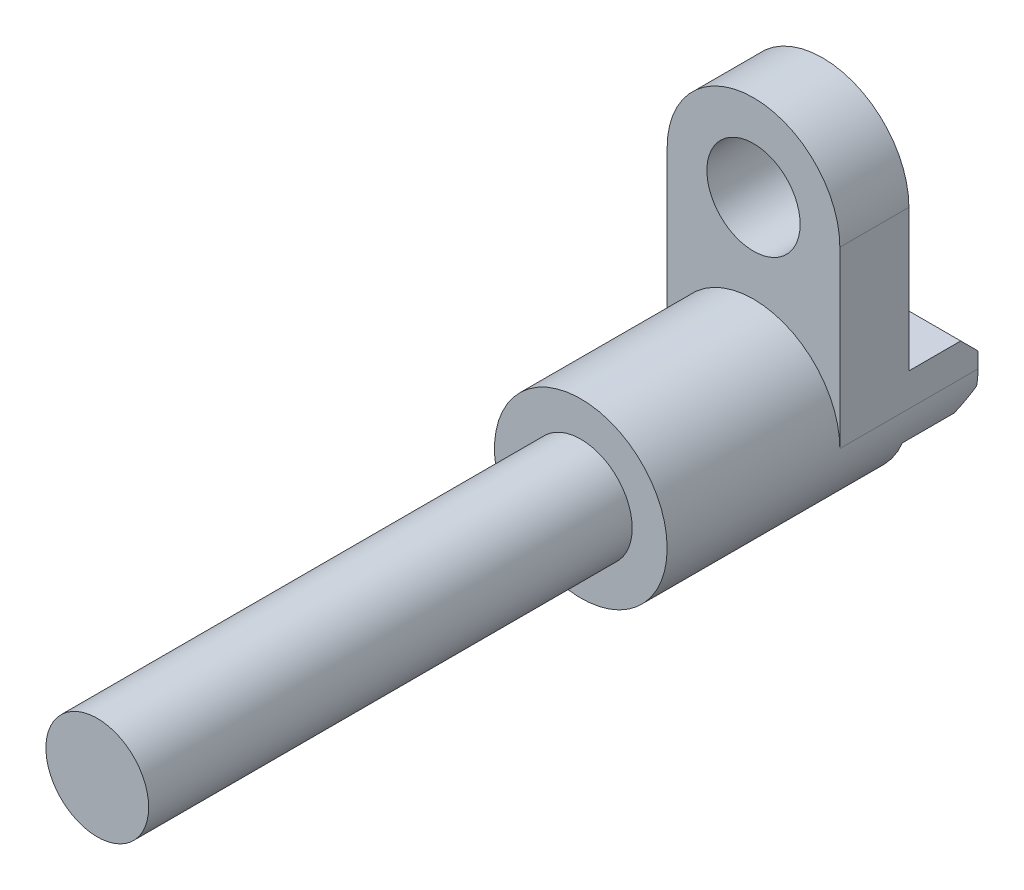
SolidWorks part; units mm, degrees
ref_plane "Front Plane" through (0, 0, 0) normal (0, 0, 1) x (1, 0, 0)
ref_plane "Top Plane" through (0, 0, 0) normal (0, 1, 0) x (1, 0, 0)
ref_plane "Right Plane" through (0, 0, 0) normal (1, 0, 0) x (0, 0, -1)
sketch "Sketch1" plane through (0, 0, 0) normal (0, 0, 1) x (1, 0, 0)
  line L0 (0, 8.6622) -> (0, -3.4189) construction
  line L1 (-7.9189, 0) -> (8.3514, 0) construction
  line L2 (-4.0536, 5.05) -> (5.1077, 5.05) construction
  line L4 (-2.5, 5.05) -> (-2.5, 0)
  line L6 (2.5, 5.05) -> (2.5, 0)
  circle A0 centre (0, 5.05) radius 1.35
  arc A1 (2.5, 5.05) -> (-2.5, 5.05) centre (0, 5.05) ccw
  arc A2 (-2.5, 0) -> (2.5, 0) centre (0, 0) ccw
  dimension "D6" = 2.7
  dimension "D1" = 2.5
  dimension "D2" = 5.05
extrude "Boss-Extrude1" add sketch "Sketch1" along normal blind 2
sketch "Sketch2" plane through (0, 0, 2) normal (0, 0, 1) x (1, 0, 0)
  line L0 (0, 8.1991) -> (0, -3.0689) construction
  line L1 (-4.5104, 0) -> (4.7191, 0) construction
  circle A1 centre (0, 0) radius 2.5
  dimension "D1" = 5
extrude "Boss-Extrude2" add sketch "Sketch2" along normal blind 5
sketch "Sketch3" plane through (0, 0, 7) normal (0, 0, 1) x (1, 0, 0)
  circle A0 centre (0, 0) radius 1.4875
  dimension "D1" = 2.975
extrude "Boss-Extrude3" add sketch "Sketch3" along normal blind 14
sketch "Sketch4" plane through (0, 0, 0) normal (0, 0, -1) x (-1, 0, 0)
  line L0 (-4.2803, 0) -> (4.6682, 0) construction
  line L1 (0, 7.8152) -> (0, -2.792) construction
  line L2 (-2.5, 0) -> (-2.5, 0.95)
  line L3 (-2.5, 0) -> (-2.5, 5.05) construction
  line L4 (-2.5, 0.95) -> (2.5, 0.95)
  line L5 (2.5, 5.05) -> (2.5, 0) construction
  line L6 (2.5, 0.95) -> (2.5, 0)
  line L7 (-2.3125, -0.95) -> (2.3125, -0.95)
  arc A0 (-2.5, 0) -> (2.5, 0) centre (0, 0) ccw construction
  arc A1 (-2.5, 0) -> (-2.3125, -0.95) centre (0, 0) ccw
  arc A2 (2.3125, -0.95) -> (2.5, 0) centre (0, 0) ccw
  dimension "D1" = 0.95
  dimension "D2" = 0.95
extrude "Boss-Extrude4" add sketch "Sketch4" along normal blind 2
chamfer "Chamfer1" distance 0.5 2 edges at (0, -0.95, -2) (0, 0.95, -2)
